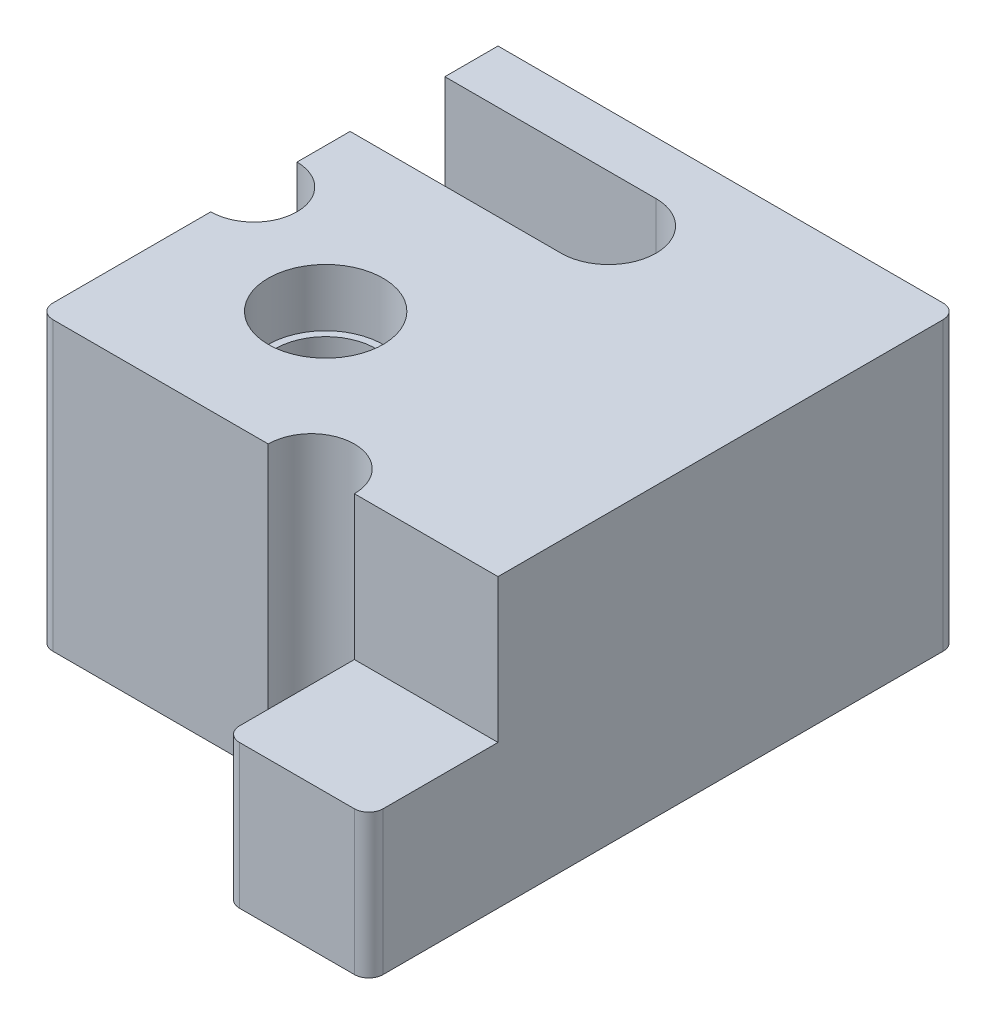
SolidWorks part; units mm, degrees
ref_plane "Front Plane" through (0, 0, 0) normal (0, 0, 1) x (1, 0, 0)
ref_plane "Top Plane" through (0, 0, 0) normal (0, 1, 0) x (1, 0, 0)
ref_plane "Right Plane" through (0, 0, 0) normal (1, 0, 0) x (0, 0, -1)
sketch "Sketch1" plane through (0, 0, 0) normal (0, 1, 0) x (1, 0, 0)
  line L1 (0, 0) -> (17, 0)
  line L2 (1, -7) -> (1, -16)
  line L3 (1, -16) -> (12, -16)
  line L6 (17, 0) -> (17, -20.5)
  line L7 (17, -20.5) -> (12, -20.5)
  line L8 (12, -16) -> (12, -20.5)
  line L9 (1, -7) -> (0, -7)
  line L10 (0, 0) -> (0, -7)
  dimension "D1" = 16
  dimension "D2" = 16
  dimension "D3" = 4.5
  dimension "D4" = 5
  dimension "D5" = 7
  dimension "D6" = 1
extrude "Boss-Extrude1" add sketch "Sketch1" along normal blind 10
sketch "Sketch4" plane through (0, 10, 0) normal (0, 1, 0) x (1, 0, 0)
  line L0 (1, -7) -> (1, -16) construction
  line L2 (1, -16) -> (12, -16) construction
  circle A0 centre (6, -11) radius 1.75
  dimension "D3" = 3.5
  dimension "D1" = 5
  dimension "D2" = 5
extrude "Cut-Extrude3" cut sketch "Sketch4" against normal blind 10
sketch "Sketch6" plane through (0, 10, 0) normal (0, 1, 0) x (1, 0, 0)
  circle A0 centre (6, -11) radius 2
  dimension "D1" = 4
extrude "Cut-Extrude5" cut sketch "Sketch6" against normal blind 2
sketch "Sketch7" plane through (0, 0, 0) normal (0, -1, 0) x (1, 0, 0)
  line L0 (0, 8.5) -> (1, 8.5) construction
  line L1 (1, 7) -> (1, 16) construction
  line L2 (0, 10) -> (1, 10)
  line L3 (0, 7) -> (1, 7)
  line L4 (0, 7) -> (1, 7) construction
  line L5 (0, 0) -> (0, 7) construction
  line L6 (10.5, 16) -> (10.5, 20.5) construction
  line L7 (1, 16) -> (12, 16) construction
  line L8 (9, 16) -> (9, 20.5)
  line L9 (12, 16) -> (12, 20.5)
  line L10 (12, 20.5) -> (17, 20.5) construction
  line L11 (12, 16) -> (12, 20.5) construction
  arc A0 (0, 10) -> (0, 7) centre (0, 8.5) ccw
  arc A1 (1, 7) -> (1, 10) centre (1, 8.5) ccw
  arc A2 (9, 16) -> (12, 16) centre (10.5, 16) ccw
  arc A3 (12, 20.5) -> (9, 20.5) centre (10.5, 20.5) ccw
  point P4 (0.5, 8.5)
  point P17 (10.5, 18.25)
  dimension "D1" = 3
  dimension "D2" = 3
extrude "Cut-Extrude6" cut sketch "Sketch7" against normal through all
sketch "Sketch8" plane through (0, 10, 0) normal (0, 1, 0) x (1, 0, 0)
  line L0 (17, -20.5) -> (17, 0) construction
  line L1 (12, -16) -> (17, -16)
  line L2 (12, -16) -> (12, -20.5)
  line L3 (12, -20.5) -> (17, -20.5)
  line L4 (17, -16) -> (17, -20.5)
  line L5 (1, -7) -> (0, -7)
  line L6 (1, -7) -> (1, 0)
  line L7 (1, 0) -> (0, 0)
  line L8 (0, -7) -> (0, 0)
  line L9 (12, -20.5) -> (17, -20.5) construction
  line L10 (0, -7) -> (1, -7) construction
  line L11 (1, -10) -> (1, -16) construction
  line L12 (1, -16) -> (9, -16) construction
  line L13 (12, -16) -> (12, -20.5) construction
extrude "Cut-Extrude7" cut sketch "Sketch8" against normal blind 5
sketch "Sketch9" plane through (0, 10, 0) normal (0, 1, 0) x (1, 0, 0)
  line L0 (8.35, -3.5) -> (0, -3.5) construction
  line L1 (8.35, -5.15) -> (0, -5.15)
  line L2 (8.35, -1.85) -> (0, -1.85)
  line L8 (0, 0) -> (0, -7) construction
  arc A0 (8.35, -5.15) -> (8.35, -1.85) centre (8.35, -3.5) ccw
  arc A1 (0, -1.85) -> (0, -5.15) centre (0, -3.5) ccw
  point P2 (4.175, -3.5)
  dimension "D1" = 1.65
  dimension "D2" = 8.35
extrude "Cut-Extrude8" cut sketch "Sketch9" against normal blind 9
fillet "Fillet6" radius 0.5 8 edges at (1, 5, 16) (17, 5, 0) (12, 2.5, 20.5) (17, 2.5, 20.5) (0, 2.5, 0) (0, 2.5, 7) (0, 3, 5.15) (0, 3, 1.85)
